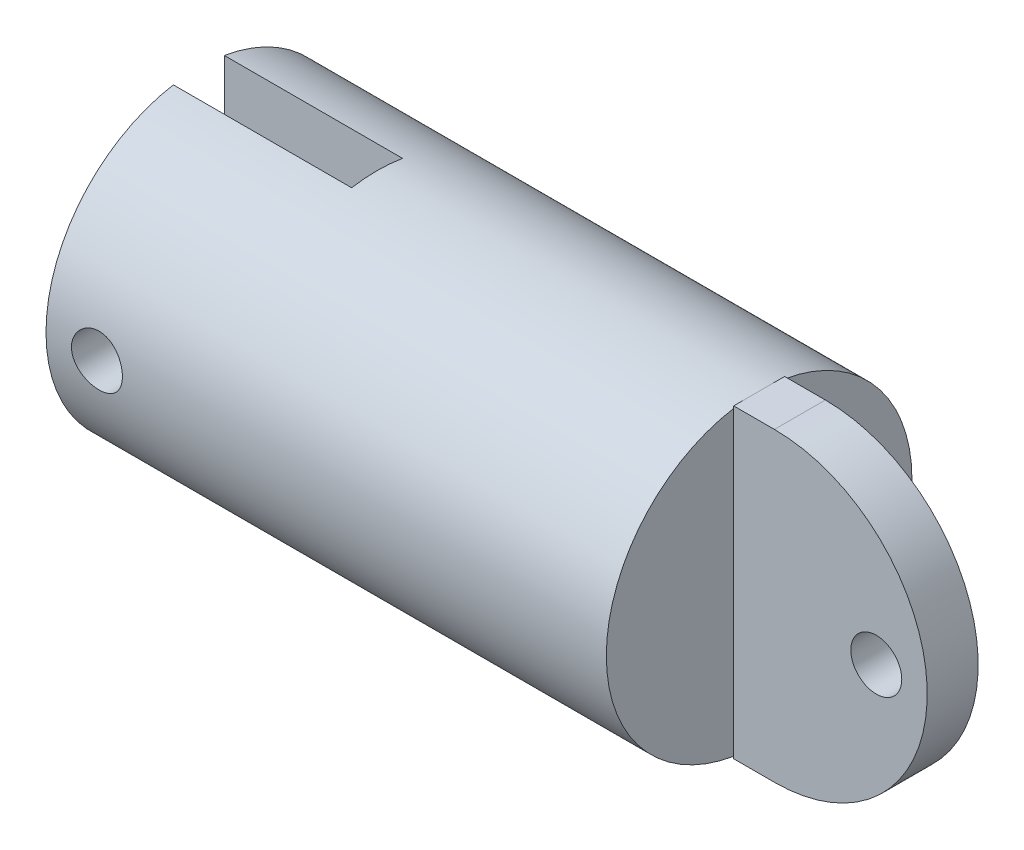
SolidWorks part; units mm, degrees
ref_plane "Front Plane" through (0, 0, 0) normal (0, 0, 1) x (1, 0, 0)
ref_plane "Top Plane" through (0, 0, 0) normal (0, 1, 0) x (1, 0, 0)
ref_plane "Right Plane" through (0, 0, 0) normal (1, 0, 0) x (0, 0, -1)
sketch "Sketch2" plane through (0, 0, 0) normal (1, 0, 0) x (0, 0, -1)
  circle A0 centre (0, 0) radius 15
  dimension "D1" = 30
extrude "Boss-Extrude1" add sketch "Sketch2" against normal blind 55
sketch "Sketch3" plane through (0, 0, 0) normal (0, 1, 0) x (1, 0, 0)
  line L0 (-55, 15) -> (-55, -15) construction
  line L1 (-55, 2.5) -> (-37.5, 2.5)
  line L2 (-55, 2.5) -> (-55, -2.5)
  line L3 (-55, -2.5) -> (-37.5, -2.5)
  line L4 (-37.5, 2.5) -> (-37.5, -2.5)
  line L5 (0, 15) -> (-55, 15) construction
  dimension "D1" = 5
  dimension "D2" = 17.5
  dimension "D3" = 0
  dimension "D4" = 12.5
extrude "Cut-Extrude1" cut sketch "Sketch3" against normal through all and the other way through all
sketch "Sketch6" plane through (0, 0, 0) normal (0, 0, 1) x (1, 0, 0)
  line L0 (-55, 14.7902) -> (-55, -14.7902) construction
  circle A0 centre (-50, 0) radius 2.5
  dimension "D2" = 5
  dimension "D1" = 5
  dimension "D3" = 0
extrude "Cut-Extrude2" cut sketch "Sketch6" against normal through all and the other way through all
sketch "Sketch7" plane through (0, 0, 0) normal (1, 0, 0) x (0, 0, -1)
  line L0 (-2.5, 15) -> (-2.5, -15)
  line L1 (-2.5, 15) -> (2.5, 15)
  line L2 (-2.5, -15) -> (2.5, -15)
  line L3 (2.5, 15) -> (2.5, -15)
  line L4 (-2.5, 15) -> (2.5, -15) construction
  line L5 (-2.5, -15) -> (2.5, 15) construction
  point P1 (0, 0)
  dimension "D1" = 5
extrude "Boss-Extrude2" add sketch "Sketch7" along normal blind 4
sketch "Sketch8" plane through (0, 0, 2.5) normal (0, 0, 1) x (1, 0, 0)
  line L0 (4, 15) -> (4, -15) construction
  line L1 (4, 15) -> (4, -15)
  arc A0 (4, -15) -> (4, 15) centre (4, 0) ccw
extrude "Boss-Extrude3" add sketch "Sketch8" against normal blind 5
sketch "Sketch9" plane through (0, 0, 2.5) normal (0, 0, 1) x (1, 0, 0)
  circle A0 centre (14, 0) radius 2.5
  arc A1 (4, -15) -> (4, 15) centre (4, 0) ccw construction
  point P5 (19, 0)
  dimension "D1" = 5
  dimension "D2" = 5
extrude "Cut-Extrude3" cut sketch "Sketch9" against normal through all and the other way through all
